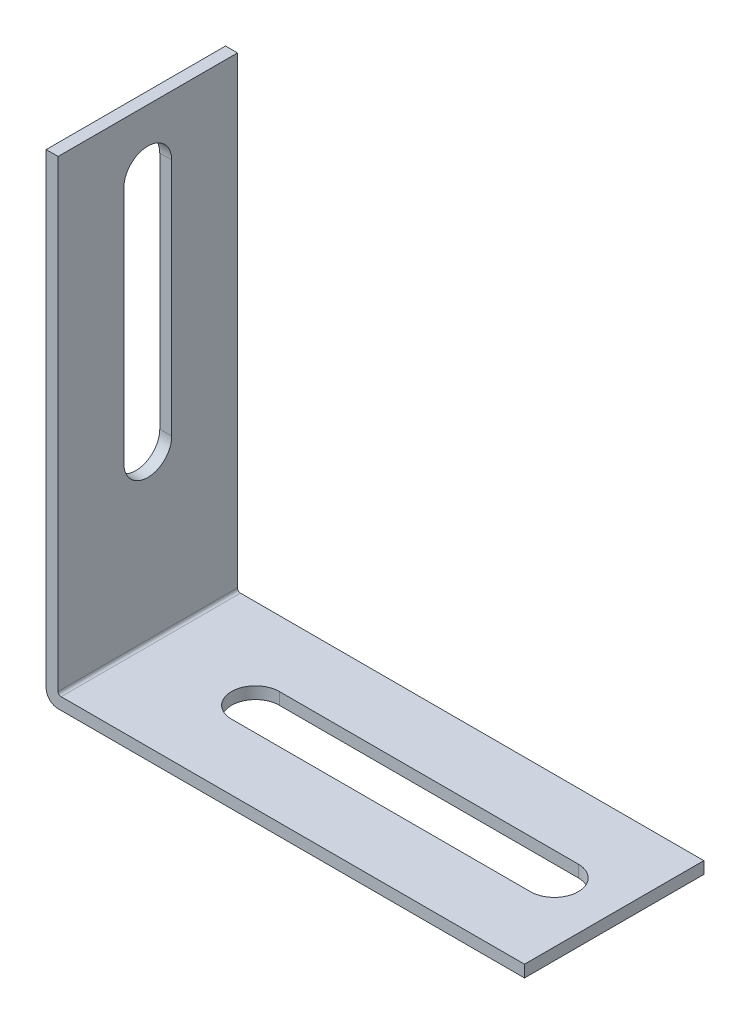
SolidWorks part; units mm, degrees
ref_plane "Front Plane" through (0, 0, 0) normal (0, 0, 1) x (1, 0, 0)
ref_plane "Top Plane" through (0, 0, 0) normal (0, 1, 0) x (1, 0, 0)
ref_plane "Right Plane" through (0, 0, 0) normal (1, 0, 0) x (0, 0, -1)
sketch "Sketch1" plane through (0, 0, 0) normal (0, 0, 1) x (1, 0, 0)
  line L0 (0, 80) -> (0, 2)
  line L1 (2, 0) -> (80, 0)
  line L2 (80, 0) -> (80, 2)
  line L3 (80, 2) -> (2.5, 2)
  line L4 (2, 2.5) -> (2, 80)
  line L5 (2, 80) -> (0, 80)
  arc A0 (0, 2) -> (2, 0) centre (2, 2) ccw
  arc A1 (2, 2.5) -> (2.5, 2) centre (2.5, 2.5) ccw
  point P9 (0, 0)
  dimension "D4" = 2
  dimension "D5" = 0.5
  dimension "D1" = 80
  dimension "D2" = 2
  dimension "D3" = 2
  dimension "D6" = 80
extrude "Boss-Extrude1" add sketch "Sketch1" along normal blind 30
sketch "Sketch2" plane through (0, 2, 0) normal (0, 1, 0) x (1, 0, 0)
  line L0 (70, -15) -> (20, -15) construction
  line L1 (70, -19) -> (20, -19)
  line L2 (70, -11) -> (20, -11)
  line L3 (80, -30) -> (80, 0) construction
  line L4 (80, -30) -> (2.5, -30) construction
  arc A0 (70, -19) -> (70, -11) centre (70, -15) ccw
  arc A1 (20, -11) -> (20, -19) centre (20, -15) ccw
  point P2 (45, -15)
  dimension "D1" = 4
  dimension "D2" = 10
  dimension "D3" = 50
  dimension "D4" = 15
extrude "Cut-Extrude1" cut sketch "Sketch2" against normal up to next
sketch "Sketch3" plane through (2, 0, 0) normal (1, 0, 0) x (0, 0, -1)
  line L0 (-15, 70) -> (-15, 30) construction
  line L1 (-11, 70) -> (-11, 30)
  line L2 (-19, 70) -> (-19, 30)
  line L3 (-30, 80) -> (0, 80) construction
  line L4 (0, 2.5) -> (0, 80) construction
  arc A0 (-11, 70) -> (-19, 70) centre (-15, 70) ccw
  arc A1 (-19, 30) -> (-11, 30) centre (-15, 30) ccw
  point P2 (-15, 50)
  dimension "D3" = 4
  dimension "D1" = 10
  dimension "D2" = 40
  dimension "D4" = 15
extrude "Cut-Extrude2" cut sketch "Sketch3" against normal up to next
